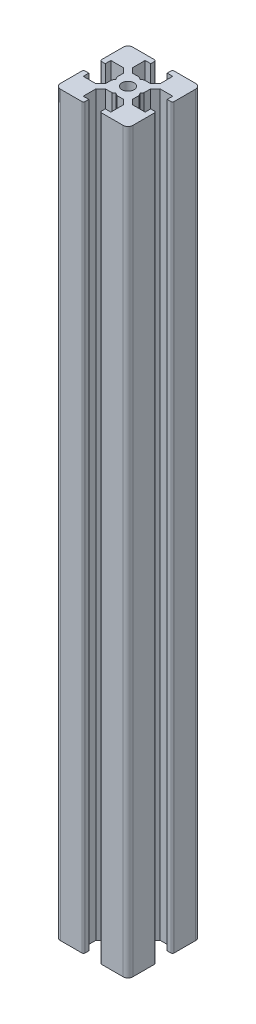
SolidWorks part; units mm, degrees
ref_plane "Front Plane" through (0, 0, 0) normal (0, 0, 1) x (1, 0, 0)
ref_plane "Top Plane" through (0, 0, 0) normal (0, 1, 0) x (1, 0, 0)
ref_plane "Right Plane" through (0, 0, 0) normal (1, 0, 0) x (0, 0, -1)
sketch "Sketch1" plane through (0, 0, 0) normal (0, 1, 0) x (1, 0, 0)
  line L0 (-7.055, 2.0047) -> (-6.255, 2.0047)
  line L1 (-6.255, 2.0047) -> (-6.255, 3.1547)
  line L2 (-6.255, 3.1547) -> (-3.655, 3.1547)
  line L3 (-3.655, 3.1547) -> (-2.655, 2.1547)
  line L4 (-2.655, 2.1547) -> (-2.655, 0.8243)
  line L5 (-2.655, 0.8243) -> (-2.355, 0.3047)
  line L6 (-2.355, 0.3047) -> (-2.655, -0.215)
  line L7 (-2.655, -0.215) -> (-2.655, -1.5453)
  line L8 (-2.655, -1.5453) -> (-3.655, -2.5453)
  line L9 (-3.655, -2.5453) -> (-6.255, -2.5453)
  line L10 (-6.255, -2.5453) -> (-6.255, -1.3953)
  line L11 (-6.255, -1.3953) -> (-7.055, -1.3953)
  line L12 (-7.355, -1.6953) -> (-7.355, -6.1953)
  line L13 (-6.355, -7.1953) -> (-1.855, -7.1953)
  line L14 (-1.555, -6.8953) -> (-1.555, -6.0953)
  line L15 (-1.555, -6.0953) -> (-2.705, -6.0953)
  line L16 (-2.705, -6.0953) -> (-2.705, -3.4953)
  line L17 (-2.705, -3.4953) -> (-1.705, -2.4953)
  line L18 (-1.705, -2.4953) -> (-0.3747, -2.4953)
  line L19 (-0.3747, -2.4953) -> (0.145, -2.1953)
  line L20 (0.145, -2.1953) -> (0.6646, -2.4953)
  line L21 (0.6646, -2.4953) -> (1.995, -2.4953)
  line L22 (1.995, -2.4953) -> (2.995, -3.4953)
  line L23 (2.995, -3.4953) -> (2.995, -6.0953)
  line L24 (2.995, -6.0953) -> (1.845, -6.0953)
  line L25 (1.845, -6.0953) -> (1.845, -6.8953)
  line L26 (2.145, -7.1953) -> (6.645, -7.1953)
  line L27 (7.645, -6.1953) -> (7.645, -1.6953)
  line L28 (7.345, -1.3953) -> (6.545, -1.3953)
  line L29 (6.545, -1.3953) -> (6.545, -2.5453)
  line L30 (6.545, -2.5453) -> (3.945, -2.5453)
  line L31 (3.945, -2.5453) -> (2.945, -1.5453)
  line L32 (2.945, -1.5453) -> (2.945, -0.215)
  line L33 (2.945, -0.215) -> (2.645, 0.3047)
  line L34 (2.645, 0.3047) -> (2.945, 0.8243)
  line L35 (2.945, 0.8243) -> (2.945, 2.1547)
  line L36 (2.945, 2.1547) -> (3.945, 3.1547)
  line L37 (3.945, 3.1547) -> (6.545, 3.1547)
  line L38 (6.545, 3.1547) -> (6.545, 2.0047)
  line L39 (6.545, 2.0047) -> (7.345, 2.0047)
  line L40 (7.645, 2.3047) -> (7.645, 6.8047)
  line L41 (6.645, 7.8047) -> (2.145, 7.8047)
  line L42 (1.845, 7.5047) -> (1.845, 6.7047)
  line L43 (1.845, 6.7047) -> (2.995, 6.7047)
  line L44 (2.995, 6.7047) -> (2.995, 4.1047)
  line L45 (2.995, 4.1047) -> (1.995, 3.1047)
  line L46 (1.995, 3.1047) -> (0.6646, 3.1047)
  line L47 (0.6646, 3.1047) -> (0.145, 2.8047)
  line L48 (0.145, 2.8047) -> (-0.3747, 3.1047)
  line L49 (-0.3747, 3.1047) -> (-1.705, 3.1047)
  line L50 (-1.705, 3.1047) -> (-2.705, 4.1047)
  line L51 (-2.705, 4.1047) -> (-2.705, 6.7047)
  line L52 (-2.705, 6.7047) -> (-1.555, 6.7047)
  line L53 (-1.555, 6.7047) -> (-1.555, 7.5047)
  line L54 (-1.855, 7.8047) -> (-6.355, 7.8047)
  line L55 (-7.355, 6.8047) -> (-7.355, 2.3047)
  arc A0 (-7.355, 2.3047) -> (-7.055, 2.0047) centre (-7.055, 2.3047) ccw
  arc A1 (-7.055, -1.3953) -> (-7.355, -1.6953) centre (-7.055, -1.6953) ccw
  arc A2 (-7.355, -6.1953) -> (-6.355, -7.1953) centre (-6.355, -6.1953) ccw
  arc A3 (-1.855, -7.1953) -> (-1.555, -6.8953) centre (-1.855, -6.8953) ccw
  arc A4 (1.845, -6.8953) -> (2.145, -7.1953) centre (2.145, -6.8953) ccw
  arc A5 (6.645, -7.1953) -> (7.645, -6.1953) centre (6.645, -6.1953) ccw
  arc A6 (7.645, -1.6953) -> (7.345, -1.3953) centre (7.345, -1.6953) ccw
  arc A7 (7.345, 2.0047) -> (7.645, 2.3047) centre (7.345, 2.3047) ccw
  arc A8 (7.645, 6.8047) -> (6.645, 7.8047) centre (6.645, 6.8047) ccw
  arc A9 (2.145, 7.8047) -> (1.845, 7.5047) centre (2.145, 7.5047) ccw
  arc A10 (-1.555, 7.5047) -> (-1.855, 7.8047) centre (-1.855, 7.5047) ccw
  arc A11 (-6.355, 7.8047) -> (-7.355, 6.8047) centre (-6.355, 6.8047) ccw
  circle A12 centre (0.145, 0.3047) radius 1.25
  point P82 (0, 0)
  point P83 (0, 0)
  point P84 (0, 0)
extrude "Boss-Extrude1" add sketch "Sketch1" along normal blind 152.4
